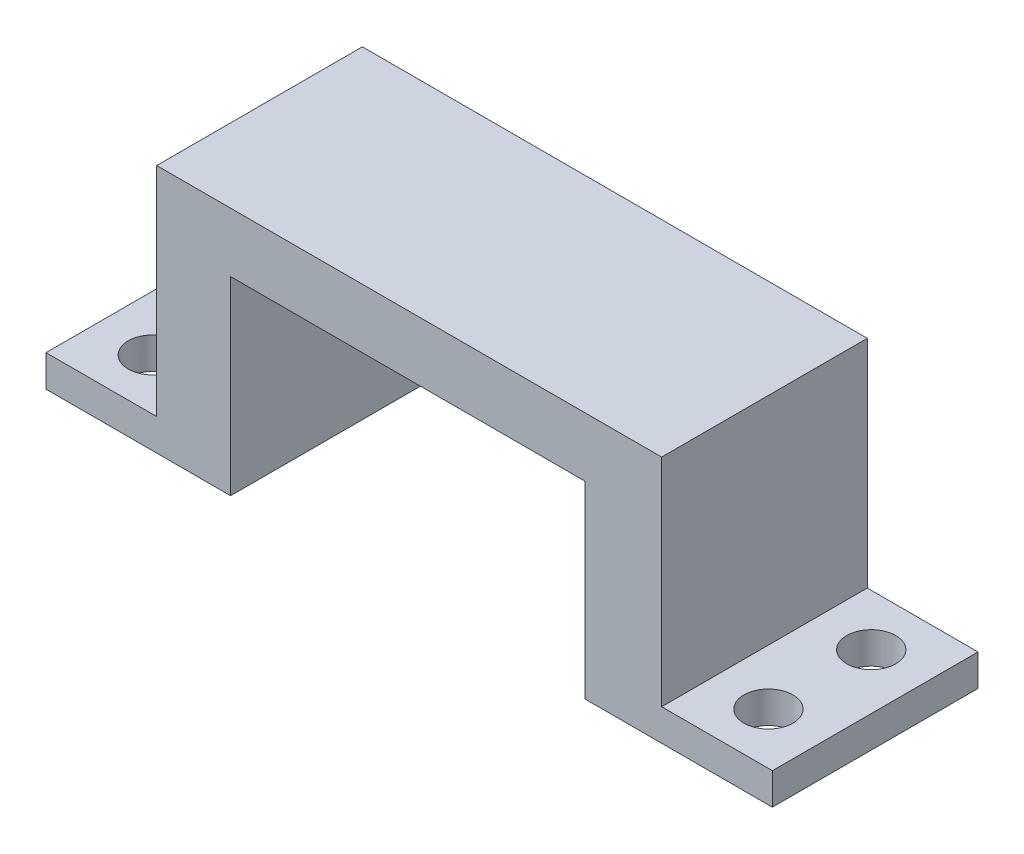
SolidWorks part; units mm, degrees
ref_plane "Front Plane" through (0, 0, 0) normal (0, 0, 1) x (1, 0, 0)
ref_plane "Top Plane" through (0, 0, 0) normal (0, 1, 0) x (1, 0, 0)
ref_plane "Right Plane" through (0, 0, 0) normal (1, 0, 0) x (0, 0, -1)
sketch "Sketch1" plane through (0, 0, 0) normal (0, 0, 1) x (1, 0, 0)
  line L0 (-44.3575, 16.746) -> (-44.3575, 20.746) construction
  line L1 (-44.3575, 17) -> (-21.9575, 17) construction
  line L2 (-49.0285, 5) -> (-44.3575, 5)
  line L3 (-49.0285, 5) -> (-49.0285, 20.746)
  line L4 (-49.0285, 20.746) -> (-44.3575, 20.746)
  line L5 (-44.3575, 5) -> (-44.3575, 20.746)
  line L6 (-49.0285, 5) -> (-44.3575, 20.746) construction
  line L7 (-49.0285, 20.746) -> (-44.3575, 5) construction
  line L10 (-44.3575, 20.746) -> (-21.9575, 20.746)
  line L11 (-44.3575, 20.746) -> (-44.3575, 17)
  line L12 (-44.3575, 17) -> (-21.9575, 17)
  line L13 (-21.9575, 20.746) -> (-21.9575, 17)
  line L14 (-44.3575, 20.746) -> (-21.9575, 17) construction
  line L15 (-44.3575, 17) -> (-21.9575, 20.746) construction
  line L16 (-21.9575, 20.746) -> (-17.1069, 20.746)
  line L17 (-21.9575, 20.746) -> (-21.9575, 5.0744)
  line L18 (-21.9575, 5.0744) -> (-17.1069, 5.0744)
  line L19 (-17.1069, 20.746) -> (-17.1069, 5.0744)
  line L20 (-21.9575, 20.746) -> (-17.1069, 5.0744) construction
  line L21 (-21.9575, 5.0744) -> (-17.1069, 20.746) construction
  line L22 (-17.1069, 5.0744) -> (-10.1069, 5.0744)
  line L23 (-17.1069, 5.0744) -> (-17.1069, 7.0744)
  line L24 (-17.1069, 7.0744) -> (-10.1069, 7.0744)
  line L25 (-10.1069, 5.0744) -> (-10.1069, 7.0744)
  line L26 (-17.1069, 5.0744) -> (-10.1069, 7.0744) construction
  line L27 (-17.1069, 7.0744) -> (-10.1069, 5.0744) construction
  line L28 (-49.0285, 5) -> (-56.0285, 5)
  line L29 (-49.0285, 5) -> (-49.0285, 7)
  line L30 (-49.0285, 7) -> (-56.0285, 7)
  line L31 (-56.0285, 5) -> (-56.0285, 7)
  line L32 (-49.0285, 5) -> (-56.0285, 7) construction
  line L33 (-49.0285, 7) -> (-56.0285, 5) construction
  point P7 (-46.693, 12.873)
  point P15 (-33.1575, 18.873)
  point P18 (-19.5322, 12.9102)
  point P25 (-13.6069, 6.0744)
  point P29 (-52.5285, 6)
  dimension "D1" = 4
  dimension "D2" = 7
  dimension "D3" = 2
  dimension "D4" = 2
  dimension "D5" = 7
extrude "Boss-Extrude1" add sketch "Sketch1" along normal blind 13 contours L2 L5 L4 L3 | L31 L28 L3 L30 | L13 L10 L5 L12 | L19 L16 L13 L17 L18 | L22 L25 L24 L19
sketch "Sketch2" plane through (0, 7.0744, 0) normal (0, 1, 0) x (1, 0, 0)
  line L0 (-10.1069, -6.5) -> (-13.6069, -6.5) construction
  line L1 (-10.1069, -13) -> (-10.1069, 0) construction
  line L2 (-13.6069, -6.5) -> (-13.6069, -9.75) construction
  line L3 (-33.0677, 0) -> (-33.0677, -13) construction
  line L4 (-49.0285, 0) -> (-17.1069, 0) construction
  line L5 (-49.0285, -13) -> (-17.1069, -13) construction
  circle A0 centre (-13.6069, -9.75) radius 1.55
  circle A1 centre (-13.6069, -3.25) radius 1.55
  circle A2 centre (-52.5285, -3.25) radius 1.55
  circle A3 centre (-52.5285, -9.75) radius 1.55
  dimension "D3" = 3.1
  dimension "D1" = 3.25
  dimension "D2" = 3.5
extrude "Cut-Extrude1" cut sketch "Sketch2" against normal through all both and the other way through all
